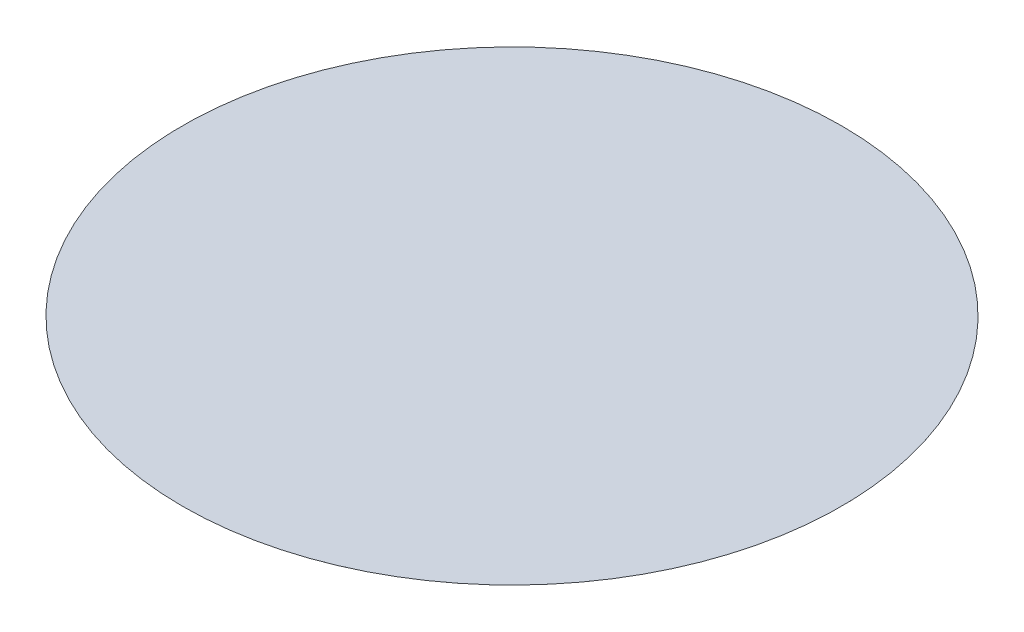
SolidWorks part; units mm, degrees
material "Brass"
ref_plane "Front Plane" through (0, 0, 0) normal (0, 0, 1) x (1, 0, 0)
ref_plane "Top Plane" through (0, 0, 0) normal (0, 1, 0) x (1, 0, 0)
ref_plane "Right Plane" through (0, 0, 0) normal (1, 0, 0) x (0, 0, -1)
sketch "Sketch1" plane through (0, 0, 0) normal (0, 1, 0) x (1, 0, 0)
  circle A0 centre (0, 0) radius 10
  dimension "D1" = 20
extrude "Boss-Extrude1" add sketch "Sketch1" along normal blind 0.0001
